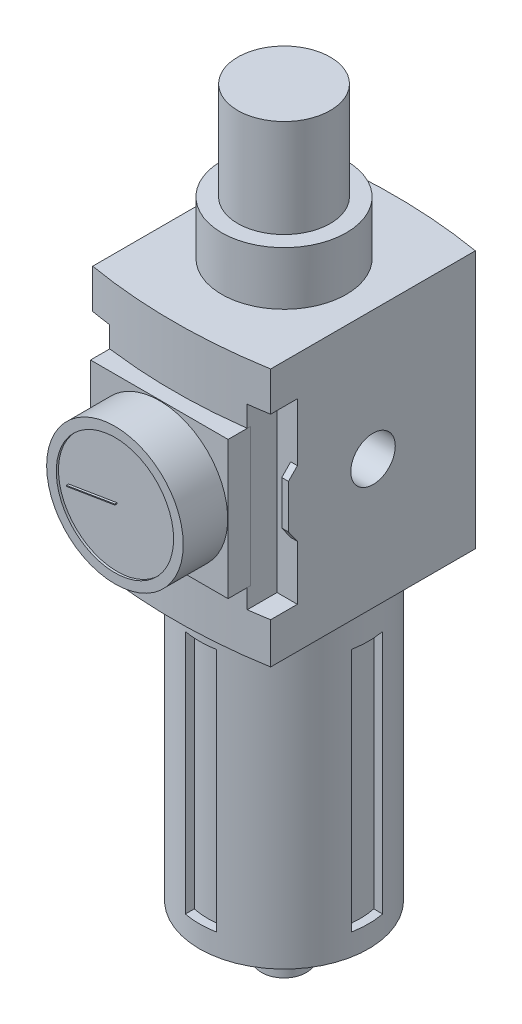
SolidWorks part; units mm, degrees
ref_plane "前视基准面" through (0, 0, 0) normal (0, 0, 1) x (1, 0, 0)
ref_plane "上视基准面" through (0, 0, 0) normal (0, 1, 0) x (1, 0, 0)
ref_plane "右视基准面" through (0, 0, 0) normal (1, 0, 0) x (0, 0, -1)
sketch "草图1" plane through (0, 0, 0) normal (0, 1, 0) x (1, 0, 0)
  circle A0 centre (0, 0) radius 19
  dimension "D1" = 38
extrude "拉伸1" add sketch "草图1" along normal blind 69
chamfer "倒角1" distance 10 angle 12 1 edges at (0, 0, 19)
sketch "草图2" plane through (0, 0, 0) normal (0, -1, 0) x (1, 0, 0)
  line L1 (5.9023, -3.628) -> (6.0931, 3.2975)
  line L2 (6.0931, 3.2975) -> (0.1908, 6.9256)
  line L3 (0.1908, 6.9256) -> (-5.9023, 3.628)
  line L4 (-5.9023, 3.628) -> (-6.0931, -3.2975)
  line L5 (-6.0931, -3.2975) -> (-0.1908, -6.9256)
  line L6 (-0.1908, -6.9256) -> (5.9023, -3.628)
  circle A0 centre (0, 0) radius 6 construction
  dimension "D1" = 12
extrude "拉伸2" add sketch "草图2" along normal blind 3.5 separate body
sketch "草图3" plane through (0, -3.5, 0) normal (0, -1, 0) x (1, 0, 0)
  circle A0 centre (0, 0) radius 5
  circle A1 centre (0, 0) radius 0.8342
  dimension "D1" = 10
extrude "拉伸3" add sketch "草图3" along normal blind 6 separate body
sketch "草图4" plane through (0, 69, 0) normal (0, 1, 0) x (1, 0, 0)
  line L2 (-20, -23) -> (-20, 23)
  line L4 (20, -23) -> (20, 23)
  line L5 (-20, -23) -> (20, 23) construction
  line L6 (-20, 23) -> (20, -23) construction
  arc A0 (-20, 23) -> (20, 23) centre (0, -95.6385) cw
  arc A1 (-20, -23) -> (20, -23) centre (0, 93.3575) ccw
  point P0 (0, 0)
  dimension "D1" = 40
  dimension "D2" = 46
extrude "拉伸4" add sketch "草图4" along normal blind 58 separate body
ref_plane "基准面1" through (0, 0, 23) normal (0, 0, 1) x (1, 0, 0)
sketch "草图5" plane through (0, 0, 23) normal (0, 0, 1) x (1, 0, 0)
  line L1 (-20, 127) -> (-20, 69) construction
  line L2 (-20, 98) -> (20, 98) construction
  line L3 (20, 127) -> (20, 69) construction
  line L5 (-15.5, 82.5) -> (15.5, 82.5)
  line L6 (-15.5, 82.5) -> (-15.5, 113.5)
  line L7 (-15.5, 113.5) -> (15.5, 113.5)
  line L8 (15.5, 82.5) -> (15.5, 113.5)
  line L9 (-15.5, 82.5) -> (15.5, 113.5) construction
  line L10 (-15.5, 113.5) -> (15.5, 82.5) construction
  point P4 (0, 98)
  dimension "D1" = 31
  dimension "D2" = 31
extrude "拉伸5" add sketch "草图5" along normal blind 5 separate body
sketch "草图6" plane through (0, 0, 28) normal (0, 0, 1) x (1, 0, 0)
  line L0 (-15.5, 98) -> (15.5, 98) construction
  line L1 (-15.5, 113.5) -> (-15.5, 82.5) construction
  line L2 (15.5, 82.5) -> (15.5, 113.5) construction
  line L3 (0, 113.5) -> (0, 82.5) construction
  line L4 (15.5, 113.5) -> (-15.5, 113.5) construction
  line L5 (-15.5, 82.5) -> (15.5, 82.5) construction
  circle A0 centre (0, 98) radius 15.35
  dimension "D1" = 30.7
extrude "拉伸6" add sketch "草图6" along normal blind 10
sketch "草图7" plane through (0, 0, 38) normal (0, 0, 1) x (1, 0, 0)
  line L0 (0, 98) -> (-10.8887, 96.2003)
  line L1 (-0.0326, 98.1973) -> (0, 98)
  line L4 (-0.0326, 98.1973) -> (-10.9213, 96.3976)
  line L5 (-10.8887, 96.2003) -> (-10.9213, 96.3976)
  circle A0 centre (0, 98) radius 13.1838
  dimension "D4" = 0.2
extrude "拉伸7" cut sketch "草图7" against normal blind 0.5
sketch "草图9" plane through (0, 127, 0) normal (0, 1, 0) x (1, 0, 0)
  circle A0 centre (0, 0) radius 14
  dimension "D1" = 28
extrude "拉伸8" add sketch "草图9" along normal blind 12
sketch "草图10" plane through (0, 139, 0) normal (0, 1, 0) x (1, 0, 0)
  circle A0 centre (0, 0) radius 10.4
  dimension "D1" = 20.8
extrude "拉伸9" add sketch "草图10" along normal blind 22
ref_plane "基准面2" through (0, 62, 0) normal (0, -1, 0) x (1, 0, 0)
sketch "草图11" plane through (0, 62, 0) normal (0, -1, 0) x (1, 0, 0)
  line L0 (16.6713, 3.5) -> (18.6748, 3.5)
  line L1 (-3.5, 16.6713) -> (-3.5, 18.6748)
  line L2 (3.5, 16.6713) -> (3.5, 18.6748)
  line L3 (16.6713, -3.5) -> (18.6748, -3.5)
  line L4 (3.5, -16.6713) -> (3.5, -18.6748)
  line L5 (-3.5, -16.6713) -> (-3.5, -18.6748)
  line L6 (-16.6713, -3.5) -> (-18.6748, -3.5)
  line L7 (-16.6713, 3.5) -> (-18.6748, 3.5)
  arc A0 (3.5, 18.6748) -> (-3.5, 18.6748) centre (0, 0) ccw
  arc A1 (3.5, 16.6713) -> (-3.5, 16.6713) centre (0, 0) ccw
  arc A2 (16.6713, -3.5) -> (16.6713, 3.5) centre (0, 0) ccw
  arc A3 (18.6748, -3.5) -> (18.6748, 3.5) centre (0, 0) ccw
  arc A4 (-3.5, -16.6713) -> (3.5, -16.6713) centre (0, 0) ccw
  arc A5 (-3.5, -18.6748) -> (3.5, -18.6748) centre (0, 0) ccw
  arc A6 (-16.6713, 3.5) -> (-16.6713, -3.5) centre (0, 0) ccw
  arc A7 (-18.6748, 3.5) -> (-18.6748, -3.5) centre (0, 0) ccw
  point P3 (-3.5, 0)
  point P4 (0, 20.4118)
  point P5 (-3.5, 20.4118)
  point P6 (3.5, 0)
  point P7 (3.5, 20.4118)
  dimension "D3" = 1.9653
extrude "拉伸11" cut sketch "草图11" along normal blind 55
sketch "草图12" plane through (0, 0, 23) normal (0, 0, 1) x (1, 0, 0)
  line L0 (20, 118.1973) -> (15.4238, 118.1973)
  line L2 (-15.4891, 78.1973) -> (-15.4891, 118.1973)
  line L4 (15.4238, 78.1973) -> (15.4238, 118.1973)
  line L5 (-15.4891, 78.1973) -> (15.4238, 118.1973) construction
  line L6 (-15.4891, 118.1973) -> (15.4238, 78.1973) construction
  line L7 (20, 127) -> (20, 69) construction
  line L8 (15.4238, 78.1973) -> (20, 78.1973)
  line L9 (20, 78.1973) -> (20, 118.1973)
  line L10 (-15.4891, 118.1973) -> (-20, 118.1973)
  line L11 (-20, 127) -> (-20, 69) construction
  line L12 (-20, 118.1973) -> (-20, 78.1973)
  line L13 (-20, 78.1973) -> (-15.4891, 78.1973)
  point P0 (-0.0326, 98.1973)
  dimension "D1" = 40
extrude "拉伸12" cut sketch "草图12" against normal mid plane 12
sketch "草图14" plane through (-20, 0, 0) normal (-1, 0, 0) x (0, 0, 1)
  line L0 (17, 78.1973) -> (17, 118.1973) construction
  line L1 (17, 105.1806) -> (17, 90.4532)
  line L4 (19, 93.2769) -> (19, 103.1178)
  line L5 (17, 98.1973) -> (19, 103.1178) construction
  line L6 (17, 98.1973) -> (19, 93.2769) construction
  line L8 (19, 103.1178) -> (17, 105.1806)
  line L9 (19, 93.2769) -> (17, 90.4532)
  point P0 (17, 98.1973)
  dimension "D1" = 2
extrude "拉伸13" add sketch "草图14" against normal blind 1.5
mirror "镜向1" about plane through (0, 0, 0) normal (1, 0, 0) of "拉伸13"
sketch "草图15" plane through (-20, 0, 0) normal (-1, 0, 0) x (0, 0, 1)
  line L0 (-23, 98) -> (19, 98.1973) construction
  line L1 (-23, 127) -> (-23, 69) construction
  line L2 (19, 93.2769) -> (19, 103.1178) construction
  line L3 (0, 127) -> (0, 87.532) construction
  line L4 (-23, 127) -> (23, 127) construction
  circle A0 centre (0, 98.1081) radius 5.5
  dimension "D1" = 11
extrude "拉伸14" cut sketch "草图15" against normal blind 6
sketch "草图16" plane through (20, 0, 0) normal (1, 0, 0) x (0, 0, -1)
  line L0 (23, 98) -> (-14.1975, 98) construction
  line L1 (23, 127) -> (23, 69) construction
  line L2 (0, 127) -> (0, 124.7354) construction
  line L3 (-23, 127) -> (23, 127) construction
  line L4 (0, 124.7354) -> (0, 89.3501) construction
  circle A0 centre (0, 98) radius 5
  dimension "D1" = 10
extrude "拉伸15" cut sketch "草图16" against normal blind 15
